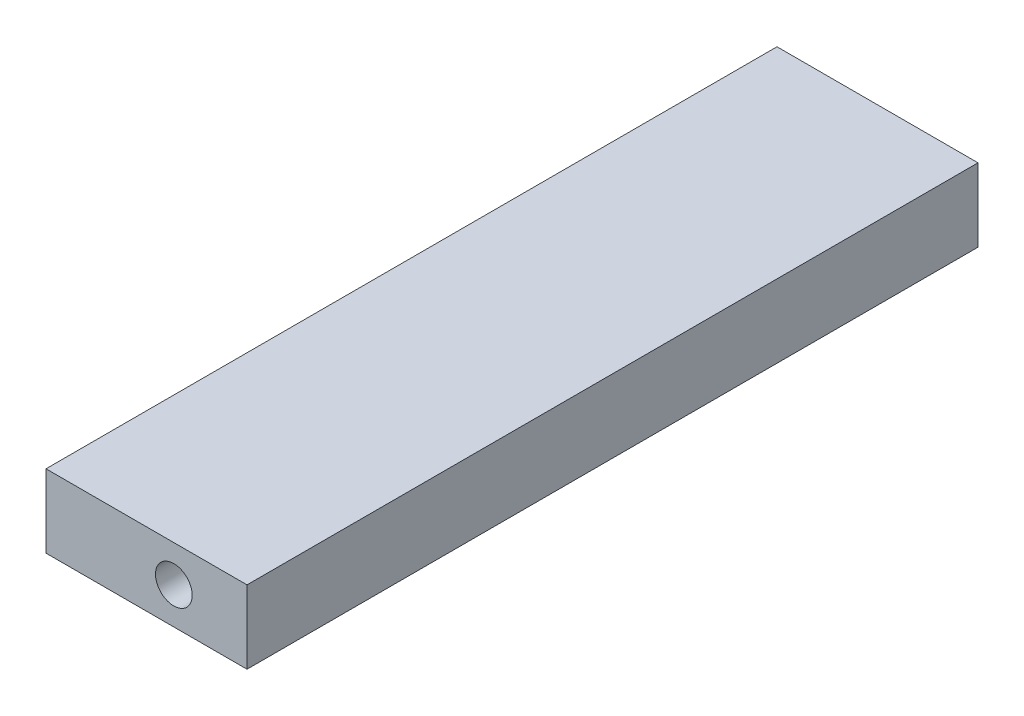
SolidWorks part; units mm, degrees
ref_plane "Front Plane" through (0, 0, 0) normal (0, 0, 1) x (1, 0, 0)
ref_plane "Top Plane" through (0, 0, 0) normal (0, 1, 0) x (1, 0, 0)
ref_plane "Right Plane" through (0, 0, 0) normal (1, 0, 0) x (0, 0, -1)
sketch "Sketch1" plane through (0, 0, 0) normal (0, 0, 1) x (1, 0, 0)
  line L1 (-13.97, -5.08) -> (13.97, -5.08)
  line L2 (-13.97, -5.08) -> (-13.97, 5.08)
  line L3 (-13.97, 5.08) -> (13.97, 5.08)
  line L4 (13.97, -5.08) -> (13.97, 5.08)
  line L5 (-13.97, -5.08) -> (13.97, 5.08) construction
  line L6 (-13.97, 5.08) -> (13.97, -5.08) construction
  point P0 (0, 0)
extrude "Boss-Extrude1" add sketch "Sketch1" along normal blind 101.6 contours L2 L1 L4 L3
ref_plane "Plane9" through (0, 0, 7.62) normal (0, 0, -1) x (-1, 0, 0)
sketch "Sketch3" plane through (0, 0, 7.62) normal (0, 0, -1) x (-1, 0, 0)
  line L0 (-13.97, -5.08) -> (-13.97, 5.08) construction
  circle A0 centre (-3.7973, 0) radius 2.5527
  point P2 (-2.3084, 0.1242)
  point P3 (0, 0)
  point P4 (0, 0)
  point P5 (0, 0)
  point P6 (0, 0)
  point P7 (0, 0)
  point P10 (-13.97, 0)
  point P11 (0, 0)
  point P12 (0, 0)
  dimension "D1" = 10.1727
  dimension "D2" = 5.1054
extrude "Cut-Extrude2" cut sketch "Sketch3" against normal through all
sketch "Sketch4" plane through (-13.97, 0, 0) normal (-1, 0, 0) x (0, 0, 1)
  line L0 (0, -5.08) -> (0, 5.08) construction
  line L1 (16.5354, 0) -> (33.0454, 0) construction
  circle A0 centre (16.5354, 0) radius 2.5527
  circle A5 centre (33.0454, 0) radius 2.5527
  circle A6 centre (49.5554, 0) radius 2.5527
  circle A15 centre (66.0654, 0) radius 2.5527
  circle A16 centre (82.5754, 0) radius 2.5527
  point P7 (0, 0)
  dimension "D1" = 16.5354
  dimension "D2" = 5.1054
  dimension "D4" = 16.51
  dimension "D3" = 5
extrude "Cut-Extrude3" cut sketch "Sketch4" against normal up to next
